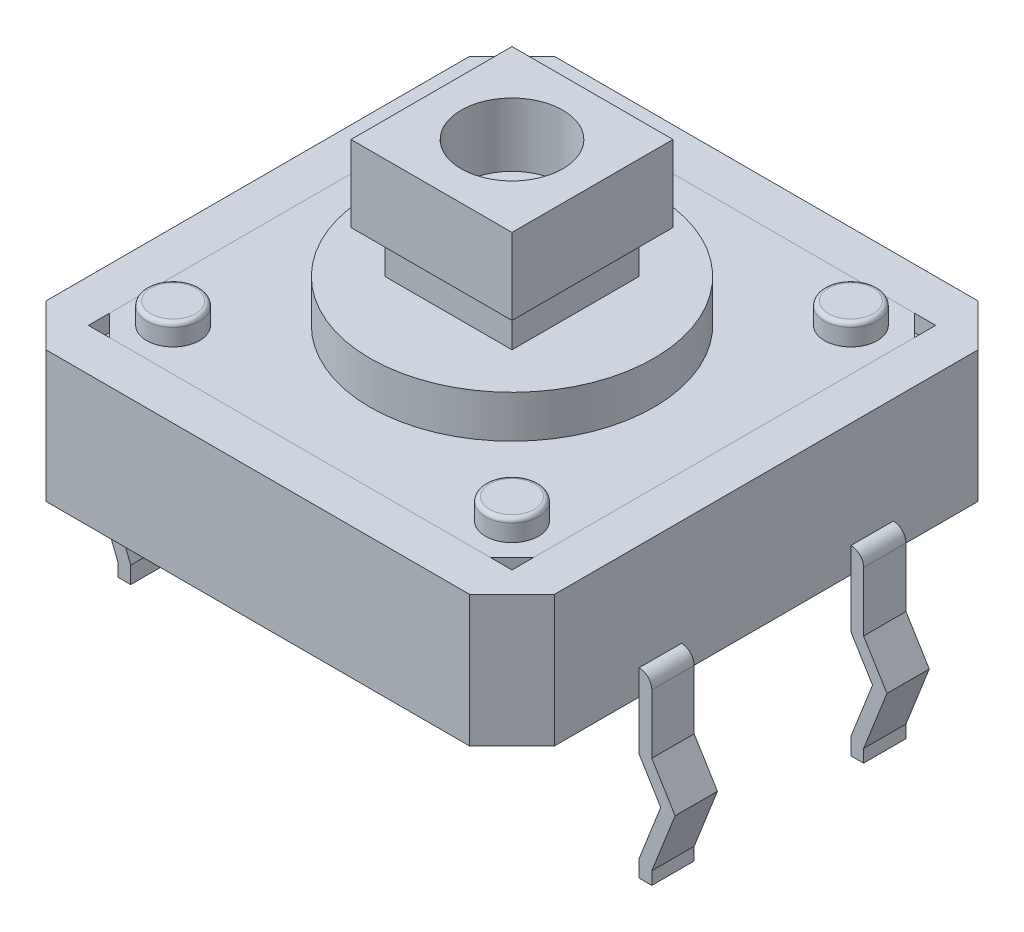
SolidWorks part; units mm, degrees
other "Markup1"
sketch "Sketch10" plane through (-6.85, 6.9, 6) normal (-0.3058, 0.046, 0.951) x (0.9335, 0.2107, 0.29)
ref_plane "Front Plane" through (0, 0, 0) normal (0, 0, 1) x (1, 0, 0)
ref_plane "Top Plane" through (0, 0, 0) normal (0, 1, 0) x (1, 0, 0)
ref_plane "Right Plane" through (0, 0, 0) normal (1, 0, 0) x (0, 0, -1)
sketch "Sketch1" plane through (0, 0, 0) normal (0, 1, 0) x (1, 0, 0)
  line L0 (-5, 6) -> (-6, 5)
  line L1 (5, -6) -> (-5, -6)
  line L2 (6, -5) -> (6, 5)
  line L3 (5, 6) -> (-5, 6)
  line L4 (-6, -5) -> (-6, 5)
  line L5 (6, -6) -> (-6, 6) construction
  line L6 (6, 6) -> (-6, -6) construction
  line L7 (-5, -6) -> (-6, -5)
  line L8 (6, -5) -> (5, -6)
  line L9 (6, 5) -> (5, 6)
  point P0 (0, 0)
  dimension "D1" = 12
extrude "Boss-Extrude1" add sketch "Sketch1" along normal blind 3.1
sketch "Sketch2" plane through (0, 3.1, 0) normal (0, 1, 0) x (1, 0, 0)
  line L1 (5, -5) -> (-5, -5)
  line L2 (5, -5) -> (5, 5)
  line L3 (5, 5) -> (-5, 5)
  line L4 (-5, -5) -> (-5, 5)
  line L5 (5, -5) -> (-5, 5) construction
  line L6 (5, 5) -> (-5, -5) construction
  point P0 (0, 0)
  point P7 (0, 0)
  point P9 (0, 0)
  point P11 (0, 0)
  point P14 (0, 0)
  point P15 (5, 4.8668)
  dimension "D1" = 10
extrude "Cut-Extrude1" cut sketch "Sketch2" against normal blind 0.4
sketch "Sketch3" plane through (0, 2.7, 0) normal (0, 1, 0) x (1, 0, 0)
  line L1 (4, -4) -> (-4, -4) construction
  line L2 (4, -4) -> (4, 4) construction
  line L3 (4, 4) -> (-4, 4) construction
  line L4 (-4, -4) -> (-4, 4) construction
  line L5 (4, -4) -> (-4, 4) construction
  line L6 (4, 4) -> (-4, -4) construction
  circle A0 centre (-4, 4) radius 0.625
  circle A1 centre (4, 4) radius 0.625
  circle A2 centre (-4, -4) radius 0.625
  circle A3 centre (4, -4) radius 0.625
  point P0 (0, 0)
  dimension "D2" = 1.25
  dimension "D1" = 8
extrude "Boss-Extrude2" add sketch "Sketch3" along normal blind 0.9
fillet "Fillet1" radius 0.1 4 edges at (4, 3.6, -3.375) (4, 3.6, 4.625) (-4, 3.6, 4.625) (-4, 3.6, -3.375)
sketch "Sketch4" plane through (0, 2.7, 0) normal (0, 1, 0) x (1, 0, 0)
  line L0 (5, 5) -> (-5, 5) construction
  line L1 (4.5, -5) -> (-4.5, -5)
  line L2 (5, -4.5) -> (5, 4.5)
  line L3 (4.5, 5) -> (-4.5, 5)
  line L4 (-5, -4.5) -> (-5, 4.5)
  line L5 (5, -5) -> (-5, 5) construction
  line L6 (5, 5) -> (-5, -5) construction
  line L9 (-5, 5) -> (-5, -5) construction
  line L10 (-4.5, 5) -> (-5, 4.5)
  line L11 (5, 4.5) -> (4.5, 5)
  line L12 (-4.5, -5) -> (-5, -4.5)
  line L13 (5, -4.5) -> (4.5, -5)
  circle A0 centre (0, 0) radius 3.35
  point P0 (0, 0)
  dimension "D2" = 6.7
extrude "Boss-Extrude3" add sketch "Sketch4" along normal blind 0.4 separate body
sketch "Sketch5" plane through (0, 0, 0) normal (0, 0, 1) x (1, 0, 0)
  line L1 (6, 3.1) -> (6, 0) construction
  line L2 (6, 0.6) -> (6, -1.1643)
  line L3 (6, -3.7) -> (6.3, -3.7)
  line L4 (6.3, -3.7) -> (6.3, -3.4)
  line L5 (6.3, -3.4) -> (6.85, -2)
  line L6 (6.85, -2) -> (6.3, -1.1)
  line L7 (6.3, -1.1) -> (6.3, 0.3)
  line L10 (6, -3.3) -> (6, -3.7)
  line L11 (6, 0.6) -> (6.3033, 0.6) construction
  line L12 (6.5107, -2) -> (6, -1.1643)
  line L13 (6, 0.3) -> (6.3, 0.3) construction
  line L14 (6.5107, -2) -> (6, -3.3)
  line L15 (0, -1.98) -> (0, 1.98) construction
  line L16 (-6, 0.3) -> (-6.3, 0.3) construction
  line L17 (-6, 0.6) -> (-6.3033, 0.6) construction
  line L18 (-6.5107, -2) -> (-6, -3.3)
  line L19 (-6.5107, -2) -> (-6, -1.1643)
  line L20 (-6, -3.3) -> (-6, -3.7)
  line L21 (-6.3, -1.1) -> (-6.3, 0.3)
  line L22 (-6.85, -2) -> (-6.3, -1.1)
  line L23 (-6.3, -3.4) -> (-6.85, -2)
  line L24 (-6.3, -3.7) -> (-6.3, -3.4)
  line L25 (-6, -3.7) -> (-6.3, -3.7)
  line L26 (-6, 0.6) -> (-6, -1.1643)
  arc A0 (6, 0.6) -> (6.3, 0.3) centre (6, 0.3) cw
  arc A1 (-6, 0.6) -> (-6.3, 0.3) centre (-6, 0.3) ccw
  point P4 (6, -0.9767)
  point P15 (6.15, -3.7)
  point P16 (0, 0)
  point P19 (6, -2.8555)
  point P20 (6.3, -2.9168)
  point P21 (0, 0)
  point P22 (6.4679, -2)
  point P23 (6, -2.7368)
  point P24 (0, 0)
  point P25 (6, -3.2574)
  point P26 (6.4257, -2)
  point P27 (6, -1.1947)
  dimension "D1" = 2.5
  dimension "D2" = 6.85
  dimension "D3" = 0.3
  dimension "D4" = 6.15
  dimension "D5" = 2
  dimension "D6" = 3.7
  dimension "D7" = 0.9
  dimension "D8" = 1.4
  dimension "D9" = 0.1
extrude "Boss-Extrude4" add sketch "Sketch5" along normal blind 3 and the other way blind 3 separate body
sketch "Sketch6" plane through (0, 0, 0) normal (0, 1, 0) x (1, 0, 0)
  line L0 (-6, 5) -> (-6, -5) construction
  line L1 (-6.85, 2) -> (-6, 2)
  line L2 (-6.85, 2) -> (-6.85, -2)
  line L3 (-6.85, -2) -> (-6, -2)
  line L4 (-6, 2) -> (-6, -2)
  line L5 (6, 2) -> (6.85, 2)
  line L6 (6, 2) -> (6, -2)
  line L7 (6, -2) -> (6.85, -2)
  line L8 (6.85, 2) -> (6.85, -2)
  line L9 (6, -5) -> (6, 5) construction
  line L10 (-6.85, 3) -> (-6.85, -3) construction
  line L11 (6.85, 3) -> (6.85, -3) construction
  point P8 (6, 0)
  point P10 (-6, 0)
  dimension "D1" = 4
extrude "Cut-Extrude2" cut sketch "Sketch6" against normal through all both and the other way through all
sketch "Sketch7" plane through (0, 2.7, 0) normal (0, 1, 0) x (1, 0, 0)
  circle A0 centre (0, 0) radius 3.35 construction
  circle A1 centre (0, 0) radius 3.35
extrude "Boss-Extrude5" add sketch "Sketch7" along normal blind 1.4 separate body
sketch "Sketch8" plane through (0, 4.1, 0) normal (0, 1, 0) x (1, 0, 0)
  line L1 (1.5, -1.5) -> (-1.5, -1.5)
  line L2 (1.5, -1.5) -> (1.5, 1.5)
  line L3 (1.5, 1.5) -> (-1.5, 1.5)
  line L4 (-1.5, -1.5) -> (-1.5, 1.5)
  line L5 (1.5, -1.5) -> (-1.5, 1.5) construction
  line L6 (1.5, 1.5) -> (-1.5, -1.5) construction
  point P0 (0, 0)
  dimension "D1" = 3
extrude "Boss-Extrude6" add sketch "Sketch8" along normal blind 1
sketch "Sketch9" plane through (0, 5.1, 0) normal (0, 1, 0) x (1, 0, 0)
  line L1 (1.9, -1.9) -> (-1.9, -1.9)
  line L2 (1.9, -1.9) -> (1.9, 1.9)
  line L3 (1.9, 1.9) -> (-1.9, 1.9)
  line L4 (-1.9, -1.9) -> (-1.9, 1.9)
  line L5 (1.9, -1.9) -> (-1.9, 1.9) construction
  line L6 (1.9, 1.9) -> (-1.9, -1.9) construction
  point P0 (0, 0)
  dimension "D1" = 3.8
extrude "Boss-Extrude7" add sketch "Sketch9" along normal blind 1.8
sketch "Sketch11" plane through (0, 6.9, 0) normal (0, 1, 0) x (1, 0, 0)
  circle A0 centre (0, 0) radius 1.2
  dimension "D1" = 2.4
extrude "Cut-Extrude3" cut sketch "Sketch11" against normal blind 1.5
sketch "Sketch12" plane through (0, 0, 0) normal (0, -1, 0) x (1, 0, 0)
  line L6 (3, 5.5) -> (3, 3.7)
  line L7 (3, 3.7) -> (5.5, 3.7)
  line L8 (5.83, 0) -> (-5.83, 0) construction
  line L9 (5.5, 4.7929) -> (5.5, -5)
  line L10 (-5, 5.5) -> (4.7929, 5.5)
  line L11 (4.7929, 5.5) -> (5.5, 4.7929)
  line L12 (5.5, 4.7929) -> (5.5, 3.7)
  line L13 (3, 5.5) -> (4.7929, 5.5)
  line L14 (4.7929, 5.5) -> (5.5, 4.7929)
  line L15 (4.7929, -5.5) -> (5.5, -4.7929)
  line L16 (3, -5.5) -> (4.7929, -5.5)
  line L17 (5.5, -4.7929) -> (5.5, -3.7)
  line L18 (3, -3.7) -> (5.5, -3.7)
  line L19 (3, -5.5) -> (3, -3.7)
  line L20 (0, -5.83) -> (0, 5.83) construction
  line L21 (-3, -5.5) -> (-3, -3.7)
  line L22 (-3, -3.7) -> (-5.5, -3.7)
  line L23 (-5.5, -4.7929) -> (-5.5, -3.7)
  line L24 (-3, -5.5) -> (-4.7929, -5.5)
  line L25 (-4.7929, -5.5) -> (-5.5, -4.7929)
  line L26 (-4.7929, 5.5) -> (-5.5, 4.7929)
  line L27 (-3, 5.5) -> (-4.7929, 5.5)
  line L28 (-5.5, 4.7929) -> (-5.5, 3.7)
  line L29 (-3, 3.7) -> (-5.5, 3.7)
  line L30 (-3, 5.5) -> (-3, 3.7)
  dimension "D2" = 2.5
  dimension "D3" = 1.8
  dimension "D1" = 0.5
extrude "Boss-Extrude8" add sketch "Sketch12" along normal blind 0.2
